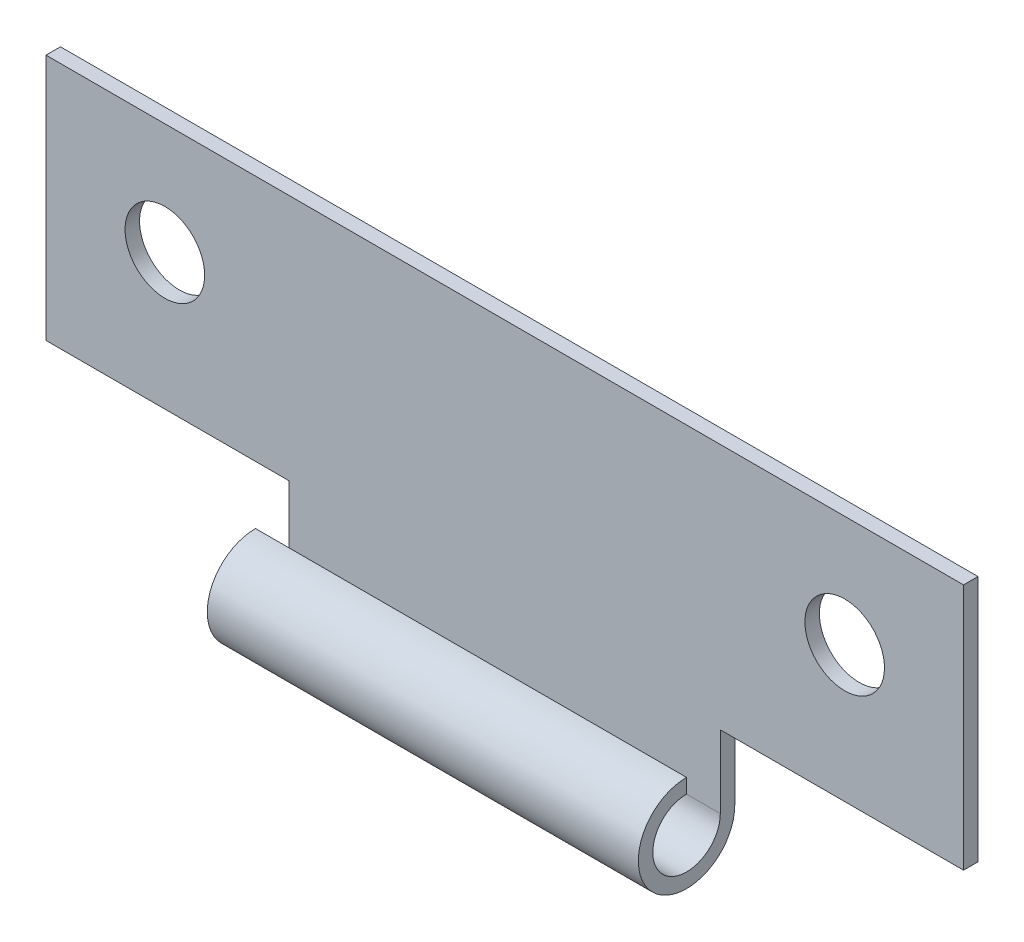
SolidWorks part; units mm, degrees
ref_plane "Front Plane" through (0, 0, 0) normal (0, 0, 1) x (1, 0, 0)
ref_plane "Top Plane" through (0, 0, 0) normal (0, 1, 0) x (1, 0, 0)
ref_plane "Right Plane" through (0, 0, 0) normal (1, 0, 0) x (0, 0, -1)
sketch "Sketch1" plane through (0, 0, 0) normal (0, 0, 1) x (1, 0, 0)
  line L1 (0, 0) -> (38.06, 0)
  line L2 (0, 0) -> (0, -10.25)
  line L3 (0, -10.25) -> (38.06, -10.25)
  line L4 (38.06, 0) -> (38.06, -10.25)
  dimension "D1" = 38.06
  dimension "D2" = 10.25
extrude "Boss-Extrude1" add sketch "Sketch1" along normal blind 0.6
sketch "Sketch2" plane through (0, 0, 0.6) normal (0, 0, 1) x (1, 0, 0)
  line L1 (0, -10.25) -> (38.06, -10.25) construction
  line L6 (38.06, -10.25) -> (38.06, 0) construction
  circle A0 centre (4.93, -4.62) radius 1.65
  circle A1 centre (33.13, -4.62) radius 1.65
  dimension "D1" = 3.3
  dimension "D2" = 3.3
  dimension "D3" = 5.63
  dimension "5.125" = 5.63
  dimension "D4" = 28.2
  dimension "D5" = 4.93
extrude "Cut-Extrude1" cut sketch "Sketch2" against normal blind 0.6
sketch "Sketch3" plane through (0, -10.25, 0) normal (0, -1, 0) x (1, 0, 0)
  line L0 (0, 0.6) -> (38.06, 0.6) construction
  line L1 (10.09, 0.6) -> (27.97, 0.6)
  line L2 (10.09, 0.6) -> (10.09, 0)
  line L3 (10.09, 0) -> (27.97, 0)
  line L4 (27.97, 0.6) -> (27.97, 0)
  line L5 (0, 0) -> (38.06, 0) construction
  line L7 (38.06, 0.6) -> (38.06, 0) construction
  dimension "D1" = 17.88
  dimension "D2" = 10.09
extrude "Boss-Extrude2" add sketch "Sketch3" along normal blind 5.01
sketch "Sketch4" plane through (27.97, 0, 0) normal (1, 0, 0) x (0, 0, -1)
  line L0 (0, -15.26) -> (0, -10.25) construction
  line L1 (0, -15.26) -> (-0.6, -15.26) construction
  line L2 (-2, -11.86) -> (-2, -11.26)
  line L3 (-0.6, -13.26) -> (0, -13.26)
  line L4 (-0.6, -15.26) -> (-0.6, -10.25) construction
  arc A0 (-2, -11.26) -> (0, -13.26) centre (-2, -13.26) ccw
  arc A1 (-2, -11.86) -> (-0.6, -13.26) centre (-2, -13.26) ccw
  dimension "D1" = 2
extrude "Boss-Extrude3" add sketch "Sketch4" against normal blind 17.88
sketch "Sketch5" plane through (27.97, 0, 0) normal (1, 0, 0) x (0, 0, -1)
  line L0 (-0.6, -14.6883) -> (-0.6, -15.26)
  line L1 (-0.6, -15.26) -> (0, -15.26)
  line L2 (0, -15.26) -> (0, -13.26)
  line L3 (0, -15.26) -> (0, -10.25) construction
  line L6 (0, -15.26) -> (0, -10.25)
  line L7 (0, -10.25) -> (-0.6, -10.25)
  line L8 (-0.6, -10.25) -> (-0.6, -13.26)
  line L9 (-2, -11.86) -> (-2, -11.26)
  line L10 (-0.6, -14.6883) -> (-0.6, -15.26)
  line L11 (-0.6, -15.26) -> (0, -15.26)
  line L12 (0, -15.26) -> (0, -10.25)
  line L13 (0, -10.25) -> (-0.6, -10.25)
  line L14 (-0.6, -10.25) -> (-0.6, -13.26)
  line L15 (-2, -11.86) -> (-2, -11.26)
  line L16 (-0.6, -14.6883) -> (-0.6, -15.26)
  line L17 (-0.6, -15.26) -> (0, -15.26)
  arc A0 (-0.6, -14.6883) -> (0, -13.26) centre (-2, -13.26) ccw
  arc A2 (-2, -11.86) -> (-0.6, -13.26) centre (-2, -13.26) ccw
  arc A3 (-2, -11.26) -> (-0.6, -14.6883) centre (-2, -13.26) ccw
  arc A4 (-2, -11.86) -> (-0.6, -13.26) centre (-2, -13.26) ccw
  arc A5 (-2, -11.26) -> (-0.6, -14.6883) centre (-2, -13.26) ccw
  line M9 (0, -15.26) -> (0, -10.25)
  line M15 (-0.6, -14.6883) -> (-0.6, -15.26)
  line M16 (-0.6, -15.26) -> (0, -15.26)
  dimension "D1" = 0
extrude "Cut-Extrude2" cut sketch "Sketch5" against normal blind 17.88 contours A0 M15 M16 M9
